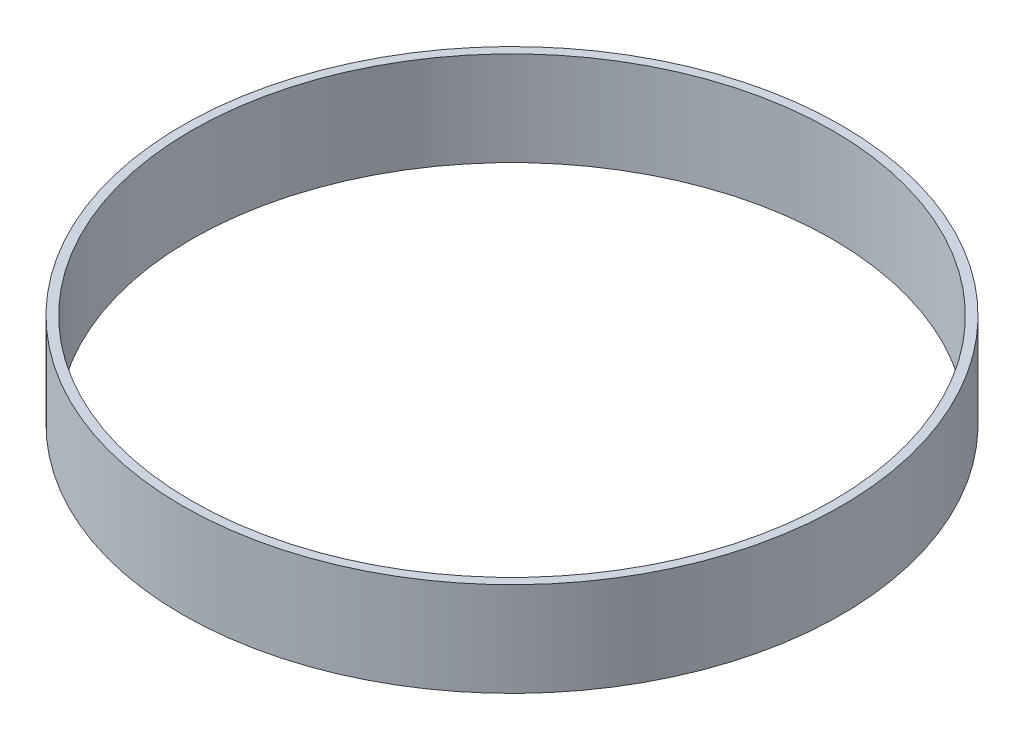
SolidWorks part; units mm, degrees
ref_plane "前视基准面" through (0, 0, 0) normal (0, 0, 1) x (1, 0, 0)
ref_plane "上视基准面" through (0, 0, 0) normal (0, 1, 0) x (1, 0, 0)
ref_plane "右视基准面" through (0, 0, 0) normal (1, 0, 0) x (0, 0, -1)
sketch "草图1" plane through (0, 0, 0) normal (0, 1, 0) x (1, 0, 0)
  circle A0 centre (0, 0) radius 34.05
  circle A1 centre (0, 0) radius 35
  dimension "D1" = 70
  dimension "D2" = 68.1
extrude "凸台-拉伸1" add sketch "草图1" along normal blind 10
